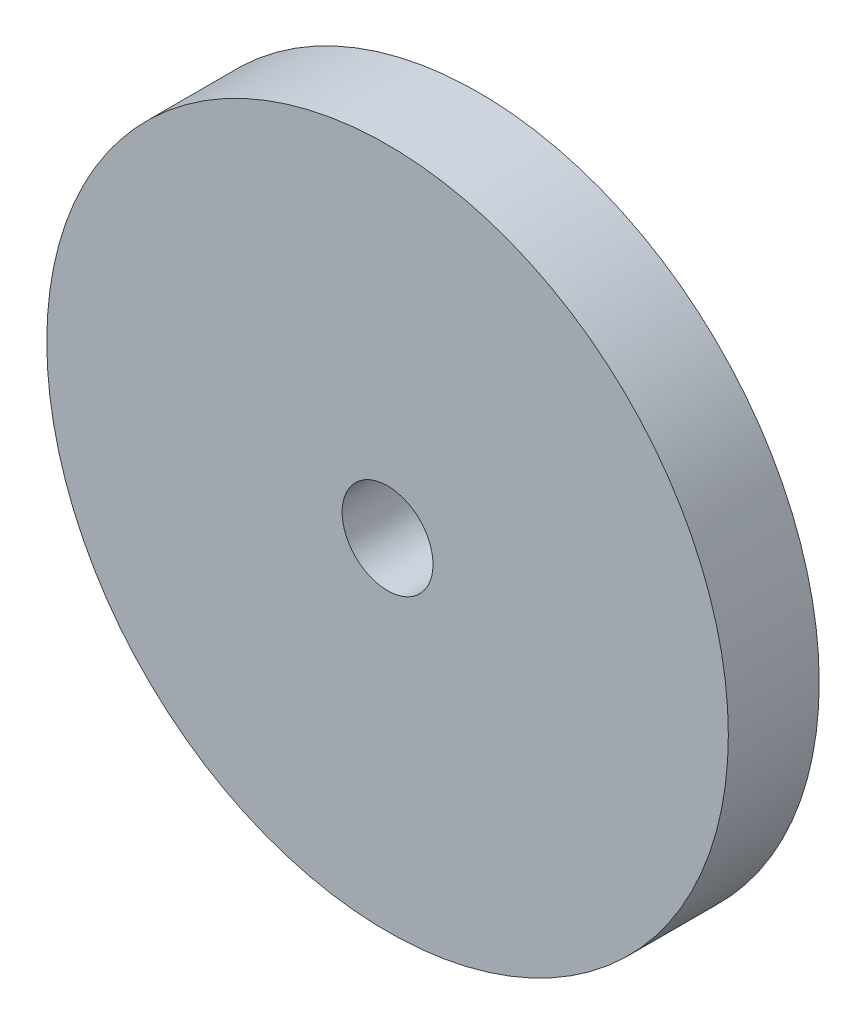
SolidWorks part; units mm, degrees
ref_plane "Front Plane" through (0, 0, 0) normal (0, 0, 1) x (1, 0, 0)
ref_plane "Top Plane" through (0, 0, 0) normal (0, 1, 0) x (1, 0, 0)
ref_plane "Right Plane" through (0, 0, 0) normal (1, 0, 0) x (0, 0, -1)
sketch "Sketch2" plane through (0, 0, 0) normal (0, 0, 1) x (1, 0, 0)
  circle A0 centre (0, 0) radius 7.5
  circle A1 centre (0, 0) radius 1
  dimension "D1" = 15
  dimension "D2" = 2
extrude "Boss-Extrude1" add sketch "Sketch2" along normal blind 2
